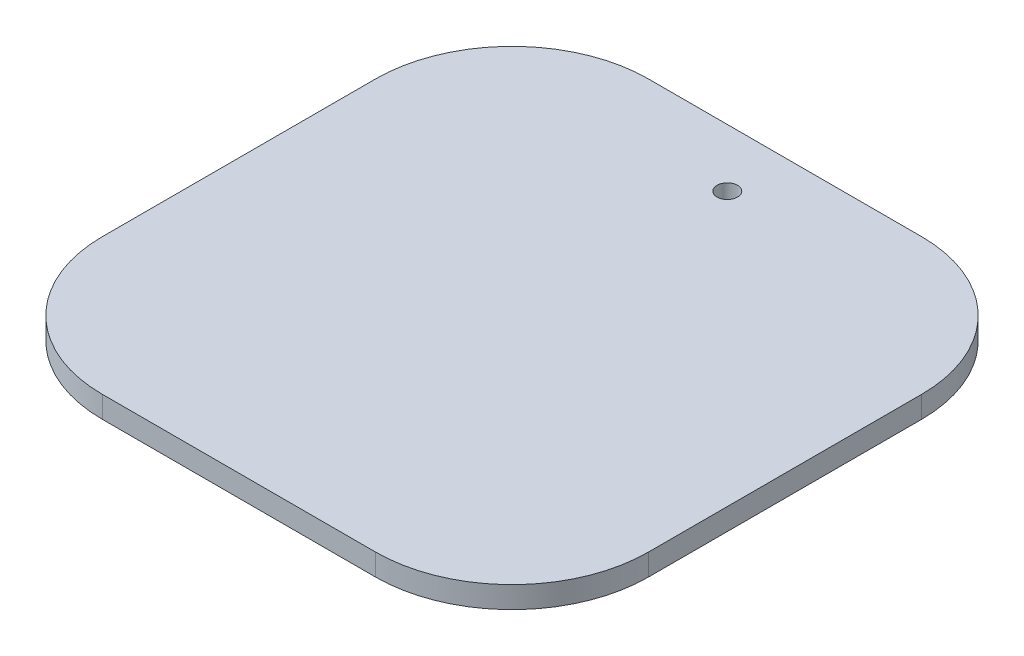
SolidWorks part; units mm, degrees
ref_plane "Front" through (0, 0, 0) normal (0, 0, 1) x (1, 0, 0)
ref_plane "Top" through (0, 0, 0) normal (0, 1, 0) x (1, 0, 0)
ref_plane "Right" through (0, 0, 0) normal (1, 0, 0) x (0, 0, -1)
sketch "Sketch1" plane through (0, 0, 0) normal (0, 1, 0) x (1, 0, 0)
  line L1 (-30, 60) -> (30, 60)
  line L2 (-60, 30) -> (-60, -30)
  line L3 (-30, -60) -> (30, -60)
  line L4 (60, 30) -> (60, -30)
  line L5 (-60, 60) -> (60, -60) construction
  line L6 (-60, -60) -> (60, 60) construction
  arc A0 (30, -60) -> (60, -30) centre (30, -30) ccw
  arc A1 (60, 30) -> (30, 60) centre (30, 30) ccw
  arc A2 (-30, 60) -> (-60, 30) centre (-30, 30) ccw
  arc A3 (-60, -30) -> (-30, -60) centre (-30, -30) ccw
  point P0 (0, 0)
  dimension "D3" = 30
  dimension "D1" = 120
  dimension "D2" = 120
extrude "Boss-Extrude1" add sketch "Sketch1" along normal blind 4.7625
hole_wizard "M4 Clearance Hole1" positions "Sketch2" profile "Sketch3" hole size "M4" standard "ANSI Metric"
sketch "Sketch2" plane through (0, 4.7625, 0) normal (0, 1, 0) x (1, 0, 0)
  line L0 (0, 60) -> (0, 47.3)
  line L1 (30, 60) -> (-30, 60) construction
  point P0 (0, 47.3)
  dimension "D1" = 12.7
sketch "Sketch3" plane through (0, 4.7625, -47.3) normal (1, 0, 0) x (0, 0, 1)
  line L0 (0, 0) -> (0, 51.3519)
  line L1 (0, 51.3519) -> (2.25, 50)
  line L2 (2.25, 50) -> (2.25, 0)
  line L5 (2.25, 0) -> (0, 0)
  line L10 (0, 51.3519) -> (-2.25, 50) construction
  line L11 (0, -6.35) -> (0, 107.95) construction
  dimension "Hole Dia." = 4.5
  dimension "Hole Depth" = 50
  dimension "Drill Angle" = 118
